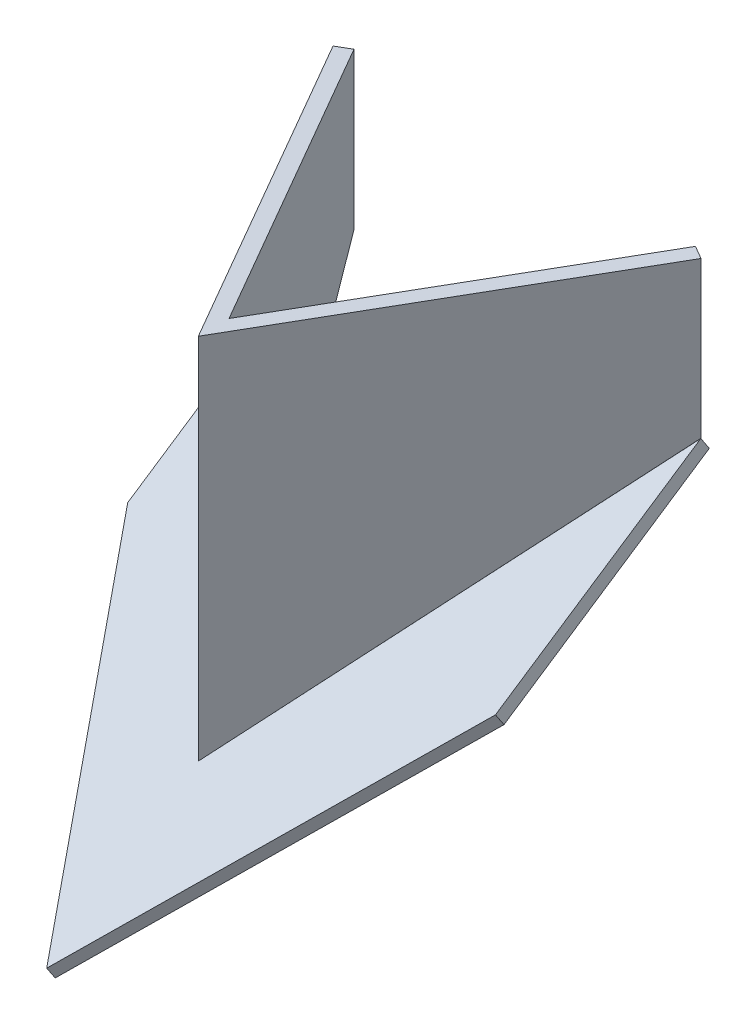
SolidWorks part; units mm, degrees
ref_plane "Front Plane" through (0, 0, 0) normal (0, 0, 1) x (1, 0, 0)
ref_plane "Top Plane" through (0, 0, 0) normal (0, 1, 0) x (1, 0, 0)
ref_plane "Right Plane" through (0, 0, 0) normal (1, 0, 0) x (0, 0, -1)
sketch "Sketch1" plane through (0, 0, 0) normal (0, 1, 0) x (1, 0, 0)
  line L0 (0, 0) -> (0, 50000) construction
  line L1 (0, 0) -> (-50000, 0)
  line L2 (0, 0) -> (76.2, 131.9823)
  line L3 (0, 0) -> (-76.2, 131.9823)
  dimension "D1" = 152.4
  dimension "D2" = 152.4
  dimension "D3" = 30
  dimension "D4" = 30
extrude "Extrude-Thin1" add sketch "Sketch1" along normal blind 152.4 thin thin type one direction wall 6.35
sketch "Sketch2" plane through (0, 0, 0) normal (0.866, 0, 0.5) x (0.5, 0, -0.866)
  line L0 (0, 0) -> (152.4, 87.9416)
  line L1 (152.4, 152.4) -> (152.4, 0) construction
  line M1 (0, 0) -> (152.4, 0)
  line M2 (152.4, 0) -> (152.4, 152.4)
sketch "Sketch3" plane through (0, 0, 0) normal (-0.866, 0, 0.5) x (0.5, 0, 0.866)
  line L0 (0, 0) -> (-152.4, 87.7371)
  line L1 (-152.4, 152.4) -> (-152.4, 0) construction
extrude "Cut-Extrude1" cut sketch "Sketch3" against normal through all and the other way through all
extrude "Cut-Extrude3" cut sketch "Sketch2" against normal through all and the other way through all contours L0 M1 M2
ref_plane "Plane4" through (0, 0, 0) normal (0.0011, -0.8325, -0.554) x (-1, -0.0009, -0.0006)
sketch "Sketch6" plane through (0, 0, 0) normal (0.0011, -0.8325, -0.554) x (-1, -0.0009, -0.0006)
  line L0 (-0.6269, -76.2) -> (76.2, 56.3386)
  line L1 (-76.2, 158.4838) -> (-76.2, 56.3386)
  line L2 (-76.2, 56.3386) -> (-0.6269, -76.2)
  line L4 (-76.2, 158.4838) -> (-76.2, 158.5971)
  line L6 (76.2, 158.4838) -> (76.2, 56.3386)
  line L7 (76.2, 158.4838) -> (0, 0)
  line L10 (0, 0) -> (-76.2, 158.4838)
extrude "Boss-Extrude1" add sketch "Sketch6" along normal blind 6.35 separate body contours L1 L2 L0 L6 L7 L10
